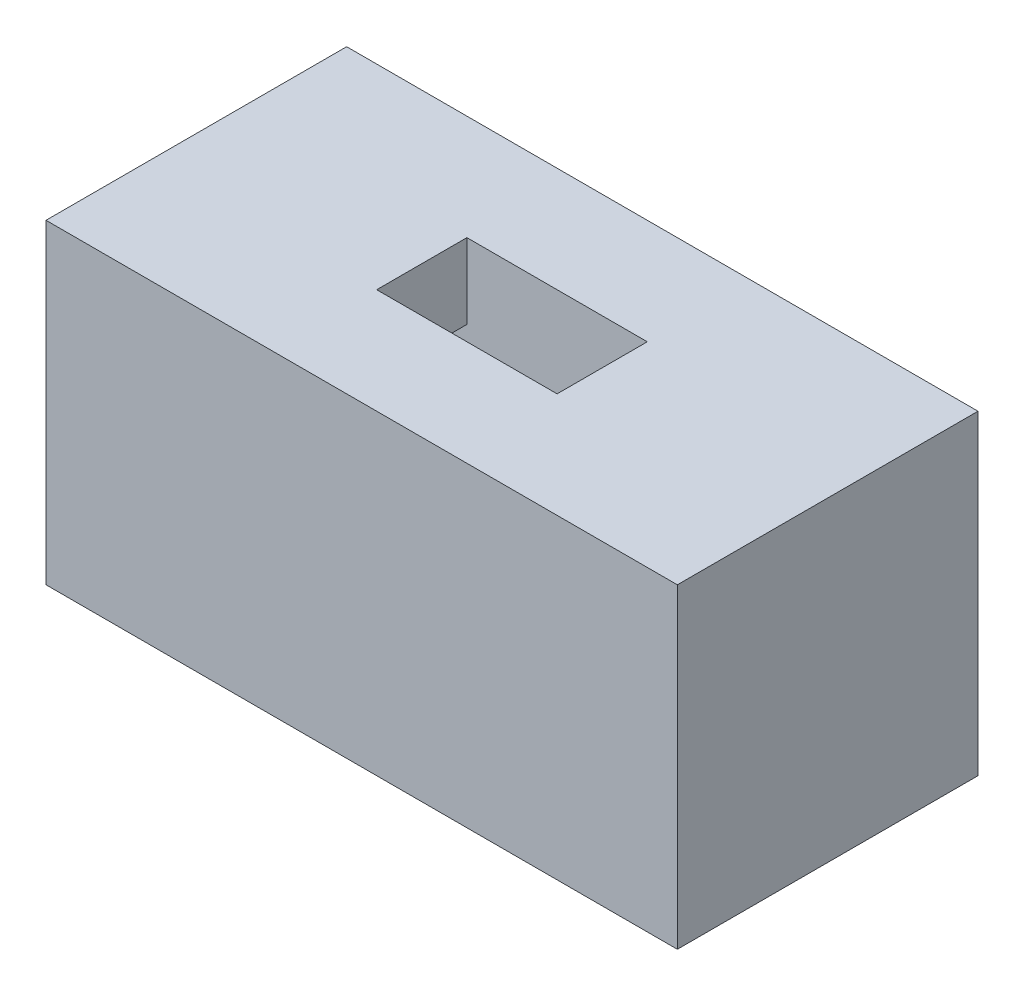
SolidWorks part; units mm, degrees
ref_plane "Plan de face" through (0, 0, 0) normal (0, 0, 1) x (1, 0, 0)
ref_plane "Plan de dessus" through (0, 0, 0) normal (0, 1, 0) x (1, 0, 0)
ref_plane "Plan de droite" through (0, 0, 0) normal (1, 0, 0) x (0, 0, -1)
sketch "Esquisse1" plane through (0, 0, 0) normal (0, 1, 0) x (1, 0, 0)
  line L1 (-21, 10) -> (21, 10)
  line L2 (-21, 10) -> (-21, -10)
  line L3 (-21, -10) -> (21, -10)
  line L4 (21, 10) -> (21, -10)
  line L5 (-21, 10) -> (21, -10) construction
  line L6 (-21, -10) -> (21, 10) construction
  point P0 (0, 0)
  dimension "D1" = 42
  dimension "D2" = 20
extrude "Boss.-Extru.1" add sketch "Esquisse1" along normal blind 21
sketch "Esquisse2" plane through (0, 21, 0) normal (0, 1, 0) x (1, 0, 0)
  line L1 (-6, -3) -> (6, -3)
  line L2 (-6, -3) -> (-6, 3)
  line L3 (-6, 3) -> (6, 3)
  line L4 (6, -3) -> (6, 3)
  line L5 (-6, -3) -> (6, 3) construction
  line L6 (-6, 3) -> (6, -3) construction
  point P0 (0, 0)
  dimension "D1" = 12
  dimension "D2" = 6
extrude "Enlèv. mat.-Extru.1" cut sketch "Esquisse2" against normal blind 10
sketch "Esquisse3" plane through (-6, 0, 0) normal (1, 0, 0) x (0, 0, -1)
  line L0 (3, 11) -> (3, 21) construction
  line L1 (-3, 11) -> (3, 11)
  line L2 (-3, 11) -> (-3, 16)
  line L3 (-3, 16) -> (3, 16)
  line L4 (3, 11) -> (3, 16)
extrude "Enlèv. mat.-Extru.2" cut sketch "Esquisse3" against normal through all
